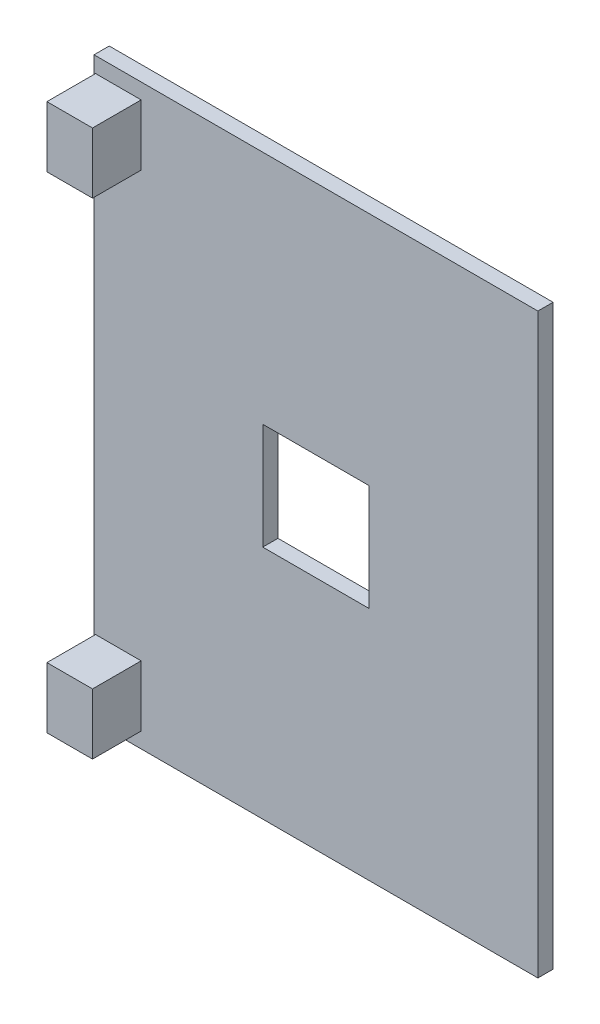
SolidWorks part; units mm, degrees
ref_plane "Plan de face" through (0, 0, 0) normal (0, 0, 1) x (1, 0, 0)
ref_plane "Plan de dessus" through (0, 0, 0) normal (0, 1, 0) x (1, 0, 0)
ref_plane "Plan de droite" through (0, 0, 0) normal (1, 0, 0) x (0, 0, -1)
sketch "Esquisse1" plane through (0, 0, 0) normal (0, 0, 1) x (1, 0, 0)
  line L1 (-108.2286, 113.1945) -> (37.7714, 113.1945)
  line L2 (-108.2286, 113.1945) -> (-108.2286, -76.8055)
  line L3 (-108.2286, -76.8055) -> (37.7714, -76.8055)
  line L4 (37.7714, 113.1945) -> (37.7714, -76.8055)
  dimension "D1" = 146
  dimension "D2" = 190
extrude "Boss.-Extru.1" add sketch "Esquisse1" along normal blind 5
sketch "Esquisse7" plane through (0, 0, 5) normal (0, 0, 1) x (1, 0, 0)
  line L3 (-108.2286, 113.1945) -> (-108.2286, -76.8055) construction
  line L4 (-108.2286, 18.1945) -> (37.7714, 18.1945) construction
  line L5 (37.7714, -76.8055) -> (37.7714, 113.1945) construction
  point P0 (-35.2286, 18.1945)
  point P4 (-35.2286, 18.1945)
sketch "Esquisse15" plane through (0, 0, 5) normal (0, 0, 1) x (1, 0, 0)
  line L0 (-108.2286, -76.8055) -> (37.7714, -76.8055) construction
  line L1 (-107.7286, -71.7055) -> (-92.7286, -71.7055)
  line L2 (-107.7286, -71.7055) -> (-107.7286, -51.7055)
  line L3 (-107.7286, -51.7055) -> (-92.7286, -51.7055)
  line L4 (-92.7286, -71.7055) -> (-92.7286, -51.7055)
  line L6 (-108.2286, 113.1945) -> (-108.2286, -76.8055) construction
  dimension "D1" = 5.1
  dimension "D2" = 20
  dimension "D3" = 0.5
  dimension "D4" = 15
extrude "Boss.-Extru.7" add sketch "Esquisse15" along normal blind 16
sketch "Esquisse16" plane through (0, 0, 5) normal (0, 0, 1) x (1, 0, 0)
  line L0 (37.7714, 113.1945) -> (-108.2286, 113.1945) construction
  line L1 (-107.7286, 108.0945) -> (-92.7286, 108.0945)
  line L2 (-107.7286, 108.0945) -> (-107.7286, 88.0945)
  line L3 (-107.7286, 88.0945) -> (-92.7286, 88.0945)
  line L4 (-92.7286, 108.0945) -> (-92.7286, 88.0945)
  line L5 (-108.2286, 113.1945) -> (-108.2286, -76.8055) construction
  dimension "D1" = 15
  dimension "D2" = 20
  dimension "D3" = 5.1
  dimension "D4" = 0.5
extrude "Boss.-Extru.8" add sketch "Esquisse16" along normal blind 16
sketch "Esquisse17" plane through (0, 0, 5) normal (0, 0, 1) x (1, 0, 0)
  line L1 (-17.7286, 0.6945) -> (-52.7286, 0.6945)
  line L2 (-17.7286, 0.6945) -> (-17.7286, 35.6945)
  line L3 (-17.7286, 35.6945) -> (-52.7286, 35.6945)
  line L4 (-52.7286, 0.6945) -> (-52.7286, 35.6945)
  line L5 (-17.7286, 0.6945) -> (-52.7286, 35.6945) construction
  line L6 (-17.7286, 35.6945) -> (-52.7286, 0.6945) construction
  point P0 (-35.2286, 18.1945)
  dimension "D1" = 35
  dimension "D2" = 35
extrude "Enlèv. mat.-Extru.1" cut sketch "Esquisse17" against normal up to surface (5 mm away) up to face at (-35.2286, 18.1945, 0)
